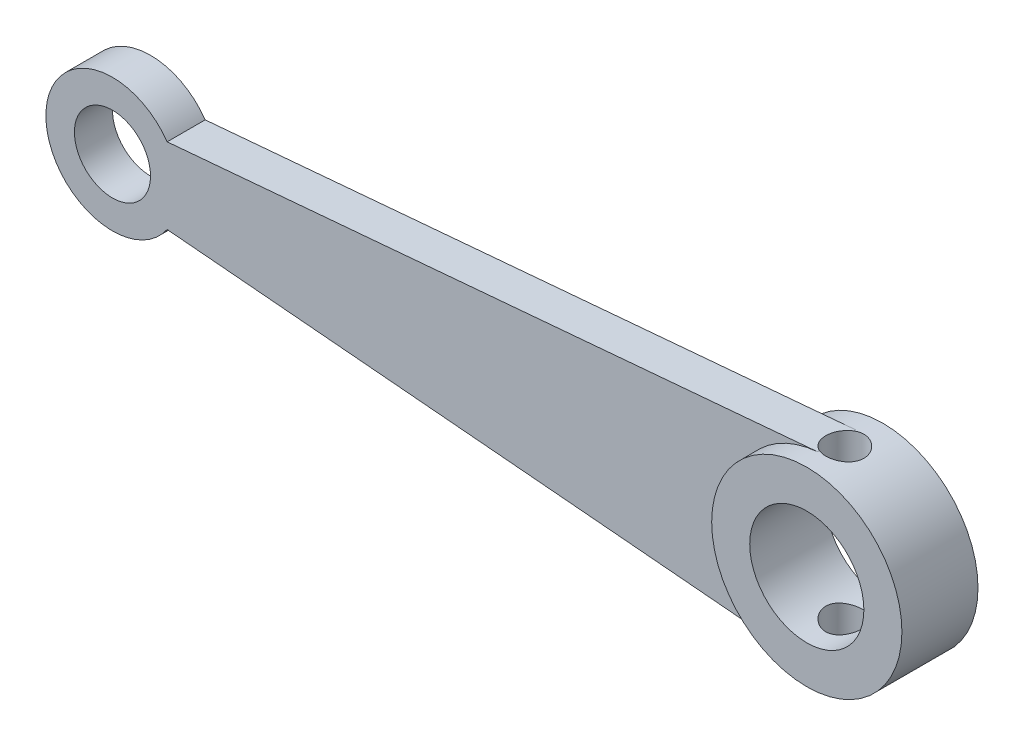
SolidWorks part; units mm, degrees
ref_plane "Front Plane" through (0, 0, 0) normal (0, 0, 1) x (1, 0, 0)
ref_plane "Top Plane" through (0, 0, 0) normal (0, 1, 0) x (1, 0, 0)
ref_plane "Right Plane" through (0, 0, 0) normal (1, 0, 0) x (0, 0, -1)
sketch "Sketch1" plane through (0, 0, 0) normal (0, 0, 1) x (1, 0, 0)
  line L2 (-34.6247, -1.9956) -> (-0.4349, -4.981)
  line L3 (-34.6247, 1.9956) -> (-0.4349, 4.981)
  circle A0 centre (0, 0) radius 5
  circle A1 centre (0, 0) radius 3
  circle A2 centre (-37.5, 0) radius 2
  arc A3 (-34.6247, 1.9956) -> (-34.6247, -1.9956) centre (-37.5, 0) ccw
  point P10 (-34.0569, 0)
  dimension "D1" = 3.5
  dimension "D2" = 4
  dimension "D3" = 10
  dimension "D4" = 6
extrude "Boss-Extrude1" add sketch "Sketch1" along normal mid plane 2 contours A0 A1 | L3 A3 L2 A0 A2
sketch "Sketch2" plane through (0, 0, 1) normal (0, 0, 1) x (1, 0, 0)
  circle A0 centre (0, 0) radius 5
extrude "Boss-Extrude2" add sketch "Sketch2" along normal mid plane 2
sketch "Sketch3" plane through (0, 0, -1) normal (0, 0, -1) x (-1, 0, 0)
  circle A0 centre (0, 0) radius 5
extrude "Boss-Extrude3" add sketch "Sketch3" along normal mid plane 2
sketch "Sketch4" plane through (0, 0, 0) normal (0, 1, 0) x (1, 0, 0)
  circle A0 centre (0, 0) radius 1
extrude "Cut-Extrude1" cut sketch "Sketch4" against normal mid plane 50
sketch "Sketch5" plane through (0, 0, -2) normal (0, 0, -1) x (-1, 0, 0)
  circle A0 centre (0, 0) radius 3
  dimension "D1" = 6
extrude "Cut-Extrude2" cut sketch "Sketch5" against normal blind 10
